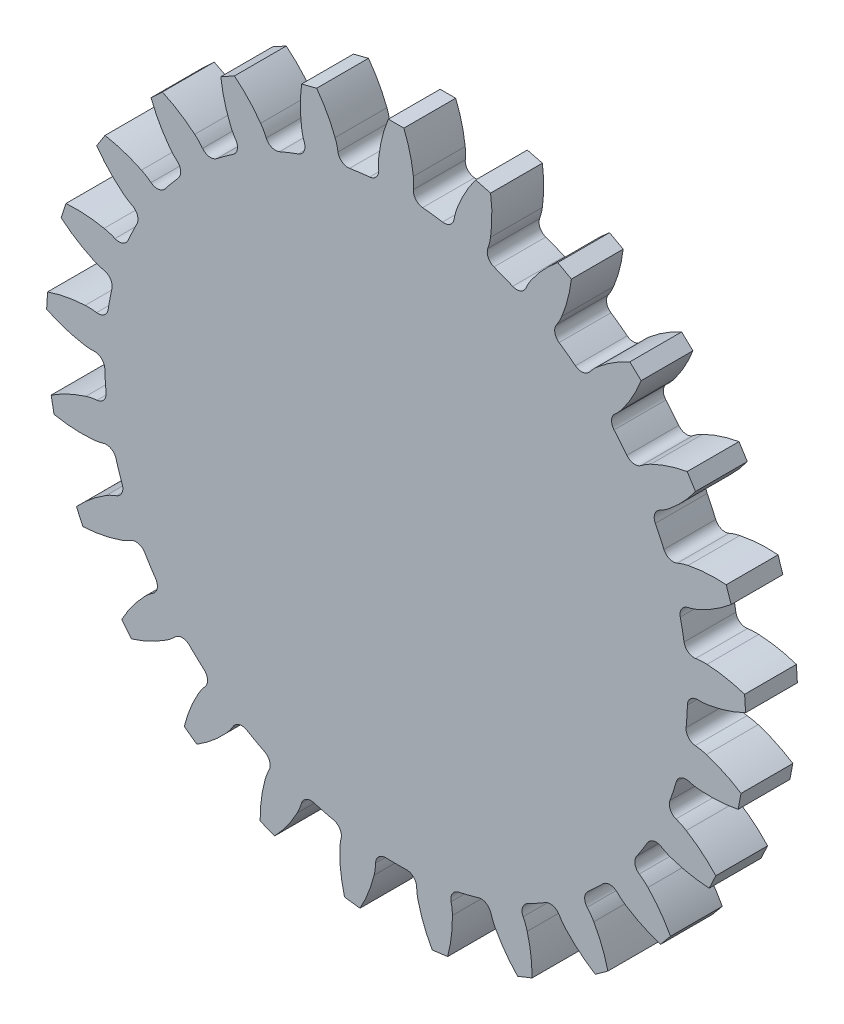
SolidWorks part; units mm, degrees
ref_plane "前视基准面" through (0, 0, 0) normal (0, 0, 1) x (1, 0, 0)
ref_plane "上视基准面" through (0, 0, 0) normal (0, 1, 0) x (1, 0, 0)
ref_plane "右视基准面" through (0, 0, 0) normal (1, 0, 0) x (0, 0, -1)
ref_plane "基准面1" through (0, 0, 3) normal (0, 0, 1) x (1, 0, 0)
sketch "草图1" plane through (0, 0, 3) normal (0, 0, 1) x (1, 0, 0)
  line L0 (17.3385, 10.4704) -> (16.8563, 11.2303)
  line L1 (14.1899, 14.4534) -> (13.5338, 15.0695)
  line L2 (10.1497, 17.5282) -> (9.361, 17.9617)
  line L3 (5.4718, 19.5016) -> (4.6, 19.7254)
  line L4 (0.45, 20.2497) -> (-0.45, 20.2497)
  line L5 (-4.6, 19.7254) -> (-5.4718, 19.5016)
  line L6 (-9.361, 17.9617) -> (-10.1497, 17.5282)
  line L7 (-13.5338, 15.0695) -> (-14.1899, 14.4534)
  line L8 (-16.8563, 11.2303) -> (-17.3385, 10.4704)
  line L9 (-19.1196, 6.6855) -> (-19.3977, 5.8295)
  line L10 (-20.1815, 1.7206) -> (-20.238, 0.8224)
  line L11 (-19.9754, -3.3524) -> (-19.8067, -4.2364)
  line L12 (-18.5141, -8.2147) -> (-18.1309, -9.0291)
  line L13 (-15.8895, -12.5609) -> (-15.3158, -13.2544)
  line L14 (-12.2665, -16.1179) -> (-11.5384, -16.6469)
  line L15 (-7.8728, -18.6621) -> (-7.036, -18.9934)
  line L16 (-2.9844, -20.0336) -> (-2.0915, -20.1464)
  line L17 (2.0915, -20.1464) -> (2.9844, -20.0336)
  line L18 (7.036, -18.9934) -> (7.8728, -18.6621)
  line L19 (11.5384, -16.6469) -> (12.2665, -16.1179)
  line L20 (15.3158, -13.2544) -> (15.8895, -12.5609)
  line L21 (18.1309, -9.0291) -> (18.5141, -8.2147)
  line L22 (19.8067, -4.2364) -> (19.9754, -3.3524)
  line L23 (20.238, 0.8224) -> (20.1815, 1.7206)
  line L24 (19.3977, 5.8295) -> (19.1196, 6.6855)
  arc A0 (16.8563, 11.2303) -> (14.7474, 10.5433) centre (18.2744, 3.2962) ccw
  arc A1 (14.7474, 10.5433) -> (14.1887, 10.1957) centre (16.1381, 7.6858) ccw
  arc A2 (14.1887, 10.1957) -> (13.3665, 10.3006) centre (13.8299, 10.6577) cw
  arc A3 (13.3665, 10.3006) -> (12.6228, 11.1996) centre (0, 0) ccw
  arc A4 (12.6228, 11.1996) -> (12.6738, 12.0269) centre (13.0604, 11.5878) cw
  arc A5 (12.6738, 12.0269) -> (13.12, 12.5105) centre (10.5736, 14.4121) ccw
  arc A6 (13.12, 12.5105) -> (14.1899, 14.4534) centre (6.6621, 17.333) ccw
  arc A7 (13.5338, 15.0695) -> (11.662, 13.8796) centre (16.8805, 7.7373) ccw
  arc A8 (11.662, 13.8796) -> (11.2074, 13.404) centre (13.7197, 11.4577) ccw
  arc A9 (11.2074, 13.404) -> (10.3849, 13.3011) centre (10.7449, 13.7622) cw
  arc A10 (10.3849, 13.3011) -> (9.441, 13.9869) centre (0, 0) ccw
  arc A11 (9.441, 13.9869) -> (9.2847, 14.8009) centre (9.7683, 14.4718) cw
  arc A12 (9.2847, 14.8009) -> (9.5965, 15.3803) centre (6.6573, 16.5888) ccw
  arc A13 (9.5965, 15.3803) -> (10.1497, 17.5282) centre (2.1422, 18.4453) ccw
  arc A14 (9.361, 17.9617) -> (7.8439, 16.3438) centre (14.426, 11.6922) ccw
  arc A15 (7.8439, 16.3438) -> (7.5218, 15.77) centre (10.4393, 14.5097) ccw
  arc A16 (7.5218, 15.77) -> (6.7508, 15.4659) centre (6.9848, 16.002) cw
  arc A17 (6.7508, 15.4659) -> (5.666, 15.8953) centre (0, 0) ccw
  arc A18 (5.666, 15.8953) -> (5.3121, 16.6449) centre (5.8624, 16.4464) cw
  arc A19 (5.3121, 16.6449) -> (5.4701, 17.2836) centre (2.3227, 17.7232) ccw
  arc A20 (5.4701, 17.2836) -> (5.4718, 19.5016) centre (-2.5122, 18.3985) ccw
  arc A21 (4.6, 19.7254) -> (3.533, 17.781) centre (11.065, 14.9125) ccw
  arc A22 (3.533, 17.781) -> (3.3637, 17.1452) centre (6.5029, 16.65) ccw
  arc A23 (3.3637, 17.1452) -> (2.6925, 16.6588) centre (2.7858, 17.2363) cw
  arc A24 (2.6925, 16.6588) -> (1.535, 16.805) centre (0, 0) ccw
  arc A25 (1.535, 16.805) -> (1.0058, 17.443) centre (1.5882, 17.3876) cw
  arc A26 (1.0058, 17.443) -> (1, 18.101) centre (-2.1579, 17.7441) ccw
  arc A27 (1, 18.101) -> (0.45, 20.2497) centre (-7.0088, 17.1957) ccw
  arc A28 (-0.45, 20.2497) -> (-1, 18.101) centre (7.0088, 17.1957) ccw
  arc A29 (-1, 18.101) -> (-1.0058, 17.443) centre (2.1579, 17.7441) ccw
  arc A30 (-1.0058, 17.443) -> (-1.535, 16.805) centre (-1.5882, 17.3876) cw
  arc A31 (-1.535, 16.805) -> (-2.6925, 16.6588) centre (0, 0) ccw
  arc A32 (-2.6925, 16.6588) -> (-3.3637, 17.1452) centre (-2.7858, 17.2363) cw
  arc A33 (-3.3637, 17.1452) -> (-3.533, 17.781) centre (-6.5029, 16.65) ccw
  arc A34 (-3.533, 17.781) -> (-4.6, 19.7254) centre (-11.065, 14.9125) ccw
  arc A35 (-5.4718, 19.5016) -> (-5.4701, 17.2836) centre (2.5122, 18.3985) ccw
  arc A36 (-5.4701, 17.2836) -> (-5.3121, 16.6449) centre (-2.3227, 17.7232) ccw
  arc A37 (-5.3121, 16.6449) -> (-5.666, 15.8953) centre (-5.8624, 16.4464) cw
  arc A38 (-5.666, 15.8953) -> (-6.7508, 15.4659) centre (0, 0) ccw
  arc A39 (-6.7508, 15.4659) -> (-7.5218, 15.77) centre (-6.9848, 16.002) cw
  arc A40 (-7.5218, 15.77) -> (-7.8439, 16.3438) centre (-10.4393, 14.5097) ccw
  arc A41 (-7.8439, 16.3438) -> (-9.361, 17.9617) centre (-14.426, 11.6922) ccw
  arc A42 (-10.1497, 17.5282) -> (-9.5965, 15.3803) centre (-2.1422, 18.4453) ccw
  arc A43 (-9.5965, 15.3803) -> (-9.2847, 14.8009) centre (-6.6573, 16.5888) ccw
  arc A44 (-9.2847, 14.8009) -> (-9.441, 13.9869) centre (-9.7683, 14.4718) cw
  arc A45 (-9.441, 13.9869) -> (-10.3849, 13.3011) centre (0, 0) ccw
  arc A46 (-10.3849, 13.3011) -> (-11.2074, 13.404) centre (-10.7449, 13.7622) cw
  arc A47 (-11.2074, 13.404) -> (-11.662, 13.8796) centre (-13.7197, 11.4577) ccw
  arc A48 (-11.662, 13.8796) -> (-13.5338, 15.0695) centre (-16.8805, 7.7373) ccw
  arc A49 (-14.1899, 14.4534) -> (-13.12, 12.5105) centre (-6.6621, 17.333) ccw
  arc A50 (-13.12, 12.5105) -> (-12.6738, 12.0269) centre (-10.5736, 14.4121) ccw
  arc A51 (-12.6738, 12.0269) -> (-12.6228, 11.1996) centre (-13.0604, 11.5878) cw
  arc A52 (-12.6228, 11.1996) -> (-13.3665, 10.3006) centre (0, 0) ccw
  arc A53 (-13.3665, 10.3006) -> (-14.1887, 10.1957) centre (-13.8299, 10.6577) cw
  arc A54 (-14.1887, 10.1957) -> (-14.7474, 10.5433) centre (-16.1381, 7.6858) ccw
  arc A55 (-14.7474, 10.5433) -> (-16.8563, 11.2303) centre (-18.2744, 3.2962) ccw
  arc A56 (-17.3385, 10.4704) -> (-15.819, 8.8547) centre (-10.7633, 15.1317) ccw
  arc A57 (-15.819, 8.8547) -> (-15.2666, 8.4972) centre (-13.8255, 11.3297) ccw
  arc A58 (-15.2666, 8.4972) -> (-15.0114, 7.7086) centre (-15.5318, 7.9758) cw
  arc A59 (-15.0114, 7.7086) -> (-15.5082, 6.6529) centre (0, 0) ccw
  arc A60 (-15.5082, 6.6529) -> (-16.2785, 6.3468) centre (-16.0458, 6.8835) cw
  arc A61 (-16.2785, 6.3468) -> (-16.9061, 6.5446) centre (-17.5424, 3.4309) ccw
  arc A62 (-16.9061, 6.5446) -> (-19.1196, 6.6855) centre (-18.52, -1.352) ccw
  arc A63 (-19.3977, 5.8295) -> (-17.5241, 4.6425) centre (-14.1883, 11.9796) ccw
  arc A64 (-17.5241, 4.6425) -> (-16.9001, 4.4336) centre (-16.2088, 7.5355) ccw
  arc A65 (-16.9001, 4.4336) -> (-16.4569, 3.7332) centre (-17.0274, 3.8626) cw
  arc A66 (-16.4569, 3.7332) -> (-16.6755, 2.5871) centre (0, 0) ccw
  arc A67 (-16.6755, 2.5871) -> (-17.3455, 2.0991) centre (-17.2536, 2.6768) cw
  arc A68 (-17.3455, 2.0991) -> (-18.0025, 2.1346) centre (-17.8445, -1.0395) ccw
  arc A69 (-18.0025, 2.1346) -> (-20.1815, 1.7206) centre (-17.6019, -5.9153) ccw
  arc A70 (-20.238, 0.8224) -> (-18.1281, 0.1385) centre (-16.7217, 8.0747) ccw
  arc A71 (-18.1281, 0.1385) -> (-17.4718, 0.0914) centre (-17.5736, 3.2678) ccw
  arc A72 (-17.4718, 0.0914) -> (-16.8683, -0.4768) centre (-17.453, -0.4933) cw
  arc A73 (-16.8683, -0.4768) -> (-16.795, -1.6412) centre (0, 0) ccw
  arc A74 (-16.795, -1.6412) -> (-17.3225, -2.2805) centre (-17.3772, -1.6981) cw
  arc A75 (-17.3225, -2.2805) -> (-17.9678, -2.4095) centre (-17.0254, -5.4446) ccw
  arc A76 (-17.9678, -2.4095) -> (-19.9754, -3.3524) centre (-15.5778, -10.1068) ccw
  arc A77 (-19.8067, -4.2364) -> (-17.593, -4.3741) centre (-18.2045, 3.6625) ccw
  arc A78 (-17.593, -4.3741) -> (-16.9456, -4.2565) centre (-17.8341, -1.2052) ccw
  arc A79 (-16.9456, -4.2565) -> (-16.2198, -4.6567) centre (-16.782, -4.8182) cw
  arc A80 (-16.2198, -4.6567) -> (-15.8592, -5.7664) centre (0, 0) ccw
  arc A81 (-15.8592, -5.7664) -> (-16.2112, -6.5168) centre (-16.409, -5.9663) cw
  arc A82 (-16.2112, -6.5168) -> (-16.8041, -6.8022) centre (-15.1365, -9.5076) ccw
  arc A83 (-16.8041, -6.8022) -> (-18.5141, -8.2147) centre (-12.575, -13.6634) ccw
  arc A84 (-18.1309, -9.0291) -> (-15.9525, -8.6119) centre (-18.5434, -0.9798) ccw
  arc A85 (-15.9525, -8.6119) -> (-15.3547, -8.337) centre (-16.9741, -5.6025) ccw
  arc A86 (-15.3547, -8.337) -> (-14.5521, -8.5441) centre (-15.0566, -8.8403) cw
  arc A87 (-14.5521, -8.5441) -> (-13.9269, -9.5292) centre (0, 0) ccw
  arc A88 (-13.9269, -9.5292) -> (-14.0812, -10.3436) centre (-14.4097, -9.8596) cw
  arc A89 (-14.0812, -10.3436) -> (-14.5845, -10.7675) centre (-12.2965, -12.9732) ccw
  arc A90 (-14.5845, -10.7675) -> (-15.8895, -12.5609) centre (-8.782, -16.3614) ccw
  arc A91 (-15.3158, -13.2544) -> (-13.3096, -12.3085) centre (-17.7171, -5.5606) ccw
  arc A92 (-13.3096, -12.3085) -> (-12.799, -11.8936) centre (-15.0475, -9.6478) ccw
  arc A93 (-12.799, -11.8936) -> (-11.9701, -11.8947) centre (-12.385, -12.307) cw
  arc A94 (-11.9701, -11.8947) -> (-11.1196, -12.6933) centre (0, 0) ccw
  arc A95 (-11.1196, -12.6933) -> (-11.0665, -13.5205) centre (-11.5051, -13.1334) cw
  arc A96 (-11.0665, -13.5205) -> (-11.4485, -14.0562) centre (-8.6839, -15.6236) ccw
  arc A97 (-11.4485, -14.0562) -> (-12.2665, -16.1179) centre (-4.4372, -18.0313) ccw
  arc A98 (-11.5384, -16.6469) -> (-9.8305, -15.2318) centre (-15.7777, -9.792) ccw
  arc A99 (-9.8305, -15.2318) -> (-9.439, -14.7029) centre (-12.1755, -13.0869) ccw
  arc A100 (-9.439, -14.7029) -> (-8.6359, -14.4978) centre (-8.9353, -15.0004) cw
  arc A101 (-8.6359, -14.4978) -> (-7.6135, -15.0599) centre (0, 0) ccw
  arc A102 (-7.6135, -15.0599) -> (-7.3564, -15.8479) centre (-7.8775, -15.5819) cw
  arc A103 (-7.3564, -15.8479) -> (-7.5932, -16.4618) centre (-4.5257, -17.2924) ccw
  arc A104 (-7.5932, -16.4618) -> (-7.8728, -18.6621) centre (0.1865, -18.5683) ccw
  arc A105 (-7.036, -18.9934) -> (-5.7337, -17.198) centre (-12.8468, -13.4081) ccw
  arc A106 (-5.7337, -17.198) -> (-5.486, -16.5884) centre (-8.5384, -15.7036) ccw
  arc A107 (-5.486, -16.5884) -> (-4.7592, -16.19) centre (-4.9241, -16.7512) cw
  arc A108 (-4.7592, -16.19) -> (-3.6291, -16.4801) centre (0, 0) ccw
  arc A109 (-3.6291, -16.4801) -> (-3.1841, -17.1794) centre (-3.7549, -17.0515) cw
  arc A110 (-3.1841, -17.1794) -> (-3.2608, -17.8329) centre (-0.083, -17.8746) ccw
  arc A111 (-3.2608, -17.8329) -> (-2.9844, -20.0336) centre (4.7983, -17.9386) ccw
  arc A112 (-2.0915, -20.1464) -> (-1.2765, -18.0836) centre (-9.1087, -16.1817) ccw
  arc A113 (-1.2765, -18.0836) -> (-1.1883, -17.4316) centre (-4.3648, -17.3337) ccw
  arc A114 (-1.1883, -17.4316) -> (-0.5834, -16.8649) centre (-0.6036, -17.4496) cw
  arc A115 (-0.5834, -16.8649) -> (0.5834, -16.8649) centre (0, 0) ccw
  arc A116 (0.5834, -16.8649) -> (1.1883, -17.4316) centre (0.6036, -17.4496) cw
  arc A117 (1.1883, -17.4316) -> (1.2765, -18.0836) centre (4.3648, -17.3337) ccw
  arc A118 (1.2765, -18.0836) -> (2.0915, -20.1464) centre (9.1087, -16.1817) ccw
  arc A119 (2.9844, -20.0336) -> (3.2608, -17.8329) centre (-4.7983, -17.9386) ccw
  arc A120 (3.2608, -17.8329) -> (3.1841, -17.1794) centre (0.083, -17.8746) ccw
  arc A121 (3.1841, -17.1794) -> (3.6291, -16.4801) centre (3.7549, -17.0515) cw
  arc A122 (3.6291, -16.4801) -> (4.7592, -16.19) centre (0, 0) ccw
  arc A123 (4.7592, -16.19) -> (5.486, -16.5884) centre (4.9241, -16.7512) cw
  arc A124 (5.486, -16.5884) -> (5.7337, -17.198) centre (8.5384, -15.7036) ccw
  arc A125 (5.7337, -17.198) -> (7.036, -18.9934) centre (12.8468, -13.4081) ccw
  arc A126 (7.8728, -18.6621) -> (7.5932, -16.4618) centre (-0.1865, -18.5683) ccw
  arc A127 (7.5932, -16.4618) -> (7.3564, -15.8479) centre (4.5257, -17.2924) ccw
  arc A128 (7.3564, -15.8479) -> (7.6135, -15.0599) centre (7.8775, -15.5819) cw
  arc A129 (7.6135, -15.0599) -> (8.6359, -14.4978) centre (0, 0) ccw
  arc A130 (8.6359, -14.4978) -> (9.439, -14.7029) centre (8.9353, -15.0004) cw
  arc A131 (9.439, -14.7029) -> (9.8305, -15.2318) centre (12.1755, -13.0869) ccw
  arc A132 (9.8305, -15.2318) -> (11.5384, -16.6469) centre (15.7777, -9.792) ccw
  arc A133 (12.2665, -16.1179) -> (11.4485, -14.0562) centre (4.4372, -18.0313) ccw
  arc A134 (11.4485, -14.0562) -> (11.0665, -13.5205) centre (8.6839, -15.6236) ccw
  arc A135 (11.0665, -13.5205) -> (11.1196, -12.6933) centre (11.5051, -13.1334) cw
  arc A136 (11.1196, -12.6933) -> (11.9701, -11.8947) centre (0, 0) ccw
  arc A137 (11.9701, -11.8947) -> (12.799, -11.8936) centre (12.385, -12.307) cw
  arc A138 (12.799, -11.8936) -> (13.3096, -12.3085) centre (15.0475, -9.6478) ccw
  arc A139 (13.3096, -12.3085) -> (15.3158, -13.2544) centre (17.7171, -5.5606) ccw
  arc A140 (15.8895, -12.5609) -> (14.5845, -10.7675) centre (8.782, -16.3614) ccw
  arc A141 (14.5845, -10.7675) -> (14.0812, -10.3436) centre (12.2965, -12.9732) ccw
  arc A142 (14.0812, -10.3436) -> (13.9269, -9.5292) centre (14.4097, -9.8596) cw
  arc A143 (13.9269, -9.5292) -> (14.5521, -8.5441) centre (0, 0) ccw
  arc A144 (14.5521, -8.5441) -> (15.3547, -8.337) centre (15.0566, -8.8403) cw
  arc A145 (15.3547, -8.337) -> (15.9525, -8.6119) centre (16.9741, -5.6025) ccw
  arc A146 (15.9525, -8.6119) -> (18.1309, -9.0291) centre (18.5434, -0.9798) ccw
  arc A147 (18.5141, -8.2147) -> (16.8041, -6.8022) centre (12.575, -13.6634) ccw
  arc A148 (16.8041, -6.8022) -> (16.2112, -6.5168) centre (15.1365, -9.5076) ccw
  arc A149 (16.2112, -6.5168) -> (15.8592, -5.7664) centre (16.409, -5.9663) cw
  arc A150 (15.8592, -5.7664) -> (16.2198, -4.6567) centre (0, 0) ccw
  arc A151 (16.2198, -4.6567) -> (16.9456, -4.2565) centre (16.782, -4.8182) cw
  arc A152 (16.9456, -4.2565) -> (17.593, -4.3741) centre (17.8341, -1.2052) ccw
  arc A153 (17.593, -4.3741) -> (19.8067, -4.2364) centre (18.2045, 3.6625) ccw
  arc A154 (19.9754, -3.3524) -> (17.9678, -2.4095) centre (15.5778, -10.1068) ccw
  arc A155 (17.9678, -2.4095) -> (17.3225, -2.2805) centre (17.0254, -5.4446) ccw
  arc A156 (17.3225, -2.2805) -> (16.795, -1.6412) centre (17.3772, -1.6981) cw
  arc A157 (16.795, -1.6412) -> (16.8683, -0.4768) centre (0, 0) ccw
  arc A158 (16.8683, -0.4768) -> (17.4718, 0.0914) centre (17.453, -0.4933) cw
  arc A159 (17.4718, 0.0914) -> (18.1281, 0.1385) centre (17.5736, 3.2678) ccw
  arc A160 (18.1281, 0.1385) -> (20.238, 0.8224) centre (16.7217, 8.0747) ccw
  arc A161 (20.1815, 1.7206) -> (18.0025, 2.1346) centre (17.6019, -5.9153) ccw
  arc A162 (18.0025, 2.1346) -> (17.3455, 2.0991) centre (17.8445, -1.0395) ccw
  arc A163 (17.3455, 2.0991) -> (16.6755, 2.5871) centre (17.2536, 2.6768) cw
  arc A164 (16.6755, 2.5871) -> (16.4569, 3.7332) centre (0, 0) ccw
  arc A165 (16.4569, 3.7332) -> (16.9001, 4.4336) centre (17.0274, 3.8626) cw
  arc A166 (16.9001, 4.4336) -> (17.5241, 4.6425) centre (16.2088, 7.5355) ccw
  arc A167 (17.5241, 4.6425) -> (19.3977, 5.8295) centre (14.1883, 11.9796) ccw
  arc A168 (19.1196, 6.6855) -> (16.9061, 6.5446) centre (18.52, -1.352) ccw
  arc A169 (16.9061, 6.5446) -> (16.2785, 6.3468) centre (17.5424, 3.4309) ccw
  arc A170 (16.2785, 6.3468) -> (15.5082, 6.6529) centre (16.0458, 6.8835) cw
  arc A171 (15.5082, 6.6529) -> (15.0114, 7.7086) centre (0, 0) ccw
  arc A172 (15.0114, 7.7086) -> (15.2666, 8.4972) centre (15.5318, 7.9758) cw
  arc A173 (15.2666, 8.4972) -> (15.819, 8.8547) centre (13.8255, 11.3297) ccw
  arc A174 (15.819, 8.8547) -> (17.3385, 10.4704) centre (10.7633, 15.1317) ccw
extrude "凸台-拉伸1" add sketch "草图1" against normal blind 3
